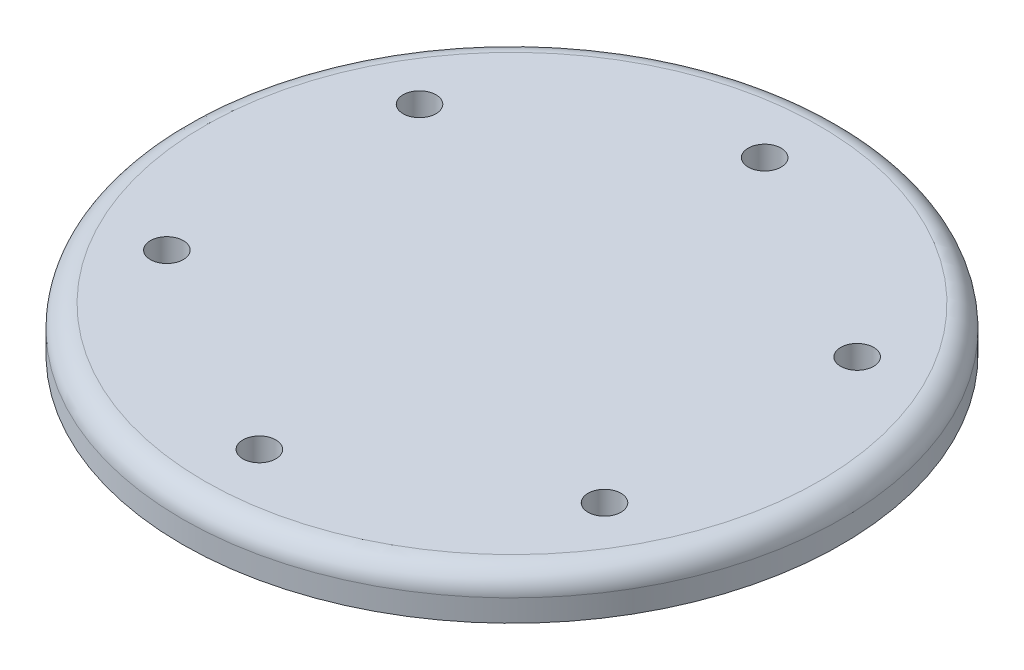
SolidWorks part; units mm, degrees
ref_plane "Front Plane" through (0, 0, 0) normal (0, 0, 1) x (1, 0, 0)
ref_plane "Top Plane" through (0, 0, 0) normal (0, 1, 0) x (1, 0, 0)
ref_plane "Right Plane" through (0, 0, 0) normal (1, 0, 0) x (0, 0, -1)
sketch "Sketch1" plane through (0, 0, 0) normal (0, 1, 0) x (1, 0, 0)
  circle A0 centre (0, 0) radius 30
  circle A1 centre (0, 0) radius 23 construction
  circle A2 centre (0, 23) radius 1.5
  circle A3 centre (19.9191, 11.5009) radius 1.5
  circle A4 centre (19.9201, -11.4991) radius 1.5
  circle A5 centre (0.002, -23) radius 1.5
  circle A6 centre (-19.9171, -11.5009) radius 1.5
  circle A7 centre (-19.9181, 11.4991) radius 1.5
  point P18 (0.001, 0)
  dimension "D1" = 60
  dimension "D2" = 46
  dimension "D3" = 3
  dimension "D4" = 6
extrude "Boss-Extrude1" add sketch "Sketch1" along normal blind 4
fillet "Fillet1" radius 2 1 edges at (0, 4, 30)
